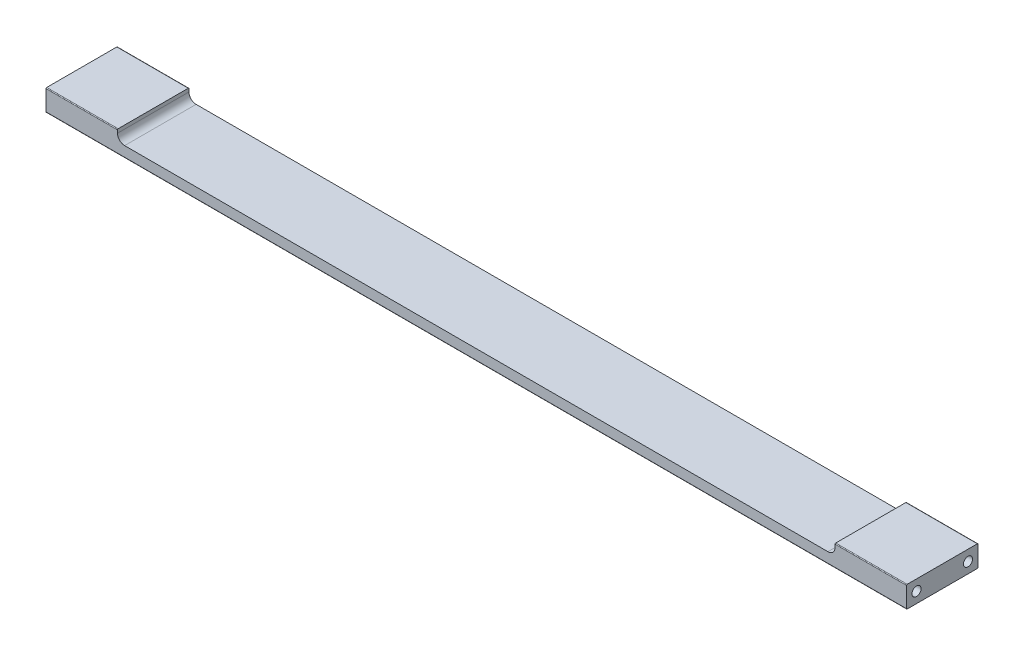
SolidWorks part; units mm, degrees
material "6061 Alloy"
ref_plane "Front Plane" through (0, 0, 0) normal (0, 0, 1) x (1, 0, 0)
ref_plane "Top Plane" through (0, 0, 0) normal (0, 1, 0) x (1, 0, 0)
ref_plane "Right Plane" through (0, 0, 0) normal (1, 0, 0) x (0, 0, -1)
sketch "Sketch1" plane through (0, 0, 0) normal (0, 1, 0) x (1, 0, 0)
  line L1 (191.135, -15.875) -> (-191.135, -15.875)
  line L2 (191.135, -15.875) -> (191.135, 15.875)
  line L3 (191.135, 15.875) -> (-191.135, 15.875)
  line L4 (-191.135, -15.875) -> (-191.135, 15.875)
  line L5 (191.135, -15.875) -> (-191.135, 15.875) construction
  line L6 (191.135, 15.875) -> (-191.135, -15.875) construction
  point P0 (0, 0)
  dimension "Length" = 382.27
  dimension "Width" = 31.75
sketch "Sketch2" plane through (0, 0, 0) normal (1, 0, 0) x (0, 0, -1)
  line L0 (15.875, 4.7625) -> (15.875, -4.7625) construction
  point P2 (15.875, 0)
  dimension "Thickness" = 9.525
sketch "Sketch3" plane through (0, 0, 0) normal (0, 1, 0) x (1, 0, 0)
  line L1 (-191.135, 15.875) -> (191.135, 15.875)
  line L2 (-191.135, 15.875) -> (-191.135, -15.875)
  line L3 (-191.135, -15.875) -> (191.135, -15.875)
  line L4 (191.135, 15.875) -> (191.135, -15.875)
extrude "Boss-Extrude1" add sketch "Sketch3" against normal up to vertex (4.7625 mm away) and the other way up to vertex (4.7625 mm away) up to point (0, -4.7625, -15.875) other way up to point (0, 4.7625, -15.875)
fillet "Fillet1" radius 0.3143 4 edges at (0, -4.7625, 15.875) (0, -4.7625, -15.875) (0, 4.7625, -15.875) (0, 4.7625, 15.875)
sketch "Sketch4" plane through (-191.135, 0, 0) normal (-1, 0, 0) x (0, 0, 1)
  line L0 (0, 0) -> (11.43, 0) construction
  line L1 (0, 0) -> (-11.43, 0) construction
  line L2 (0, 0) -> (0, 2.7298) construction
  dimension "D1" = 11.43
  dimension "D2" = 11.43
hole_wizard "Tap Drill for #10-32 Tap1" positions "Sketch5" profile "Sketch6" hole size "#10-32" standard "ANSI Inch"
sketch "Sketch5" plane through (-191.135, 0, 0) normal (-1, 0, 0) x (0, 0, 1)
  point P0 (-11.43, 0)
  point P3 (11.43, 0)
sketch "Sketch6" plane through (-191.135, 0, -11.43) normal (0, 1, 0) x (0, 0, 1)
  line L0 (0, 0) -> (0, 26.6133)
  line L1 (0, 26.6133) -> (2.0193, 25.4)
  line L2 (2.0193, 25.4) -> (2.0193, 0)
  line L5 (2.0193, 0) -> (0, 0)
  line L10 (0, 26.6133) -> (-2.0193, 25.4) construction
  line L11 (0, -6.35) -> (0, 107.95) construction
  dimension "Hole Dia." = 4.0386
  dimension "Hole Depth" = 25.4
  dimension "Drill Angle" = 118
hole_wizard "Tap Drill for #10-32 Tap2" positions "Sketch7" profile "Sketch8" hole size "#10-32" standard "ANSI Inch"
sketch "Sketch7" plane through (191.135, 0, 0) normal (1, 0, 0) x (0, 0, -1)
  point P0 (-11.43, 0)
  point P3 (11.43, 0)
sketch "Sketch8" plane through (191.135, 0, 11.43) normal (0, 1, 0) x (0, 0, -1)
  line L0 (0, 0) -> (0, 26.6133)
  line L1 (0, 26.6133) -> (2.0193, 25.4)
  line L2 (2.0193, 25.4) -> (2.0193, 0)
  line L5 (2.0193, 0) -> (0, 0)
  line L10 (0, 26.6133) -> (-2.0193, 25.4) construction
  line L11 (0, -6.35) -> (0, 107.95) construction
  dimension "Hole Dia." = 4.0386
  dimension "Hole Depth" = 25.4
  dimension "Drill Angle" = 118
sketch "Sketch9" plane through (0, 0, -15.875) normal (0, 0, -1) x (-1, 0, 0)
  line L0 (159.385, 4.7625) -> (159.385, 3.175)
  line L7 (-191.135, 4.7625) -> (191.135, 4.7625) construction
  line L8 (156.21, 0) -> (-156.21, 0)
  line L9 (-159.385, 3.175) -> (-159.385, 4.7625)
  line L10 (-159.385, 4.7625) -> (159.385, 4.7625)
  line L11 (191.135, 113.2576) -> (191.135, 38.2159) construction
  line L12 (-191.135, 113.2576) -> (-191.135, 38.2159) construction
  arc A0 (159.385, 3.175) -> (156.21, 0) centre (156.21, 3.175) cw
  arc A1 (-156.21, 0) -> (-159.385, 3.175) centre (-156.21, 3.175) cw
  point P15 (159.385, 0)
  point P18 (-159.385, 0)
  dimension "D4" = 3.175
  dimension "D1" = 31.75
  dimension "D2" = 31.75
  dimension "D3" = 4.7625
extrude "Cut-Extrude1" cut sketch "Sketch9" against normal through all
equation "\"D1@Fillet1\" = \"Thickness@Sketch2\" * .033"
